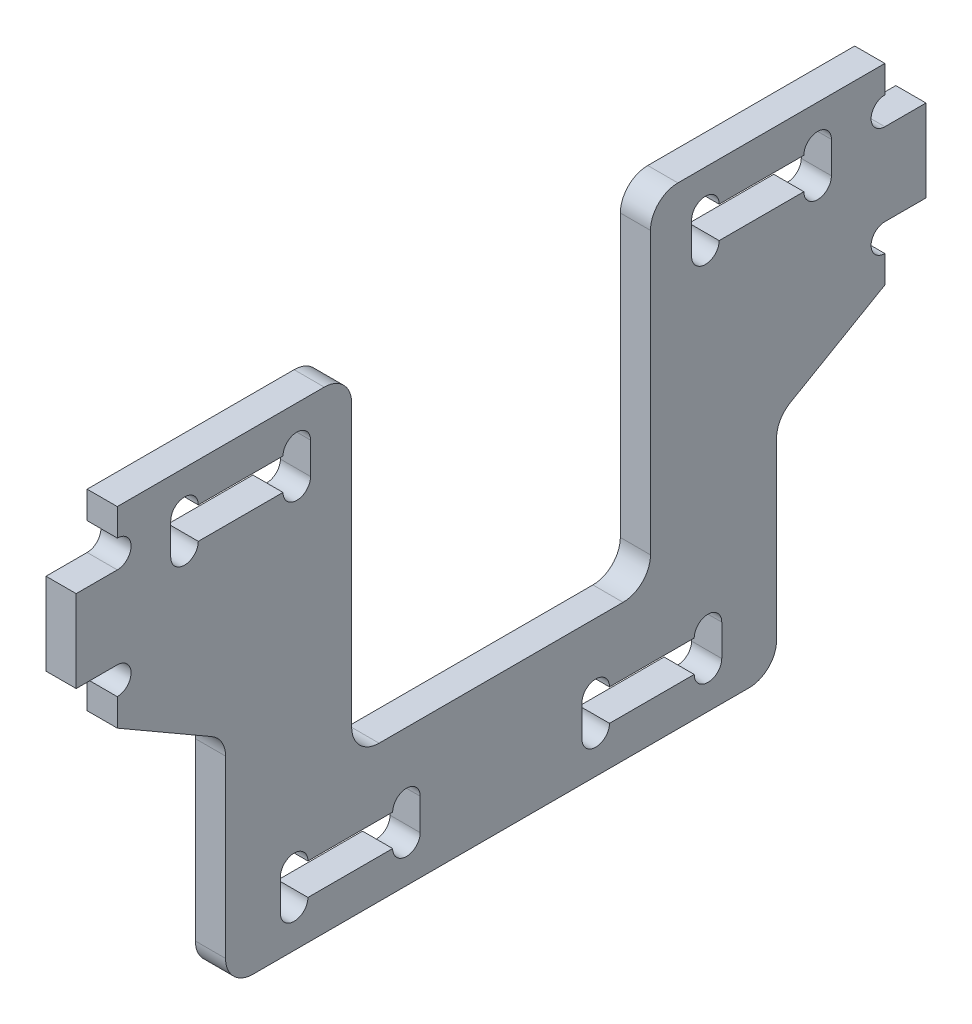
SolidWorks part; units mm, degrees
material "Thornel Mat VMA"
ref_plane "前视基准面" through (0, 0, 0) normal (0, 0, 1) x (1, 0, 0)
ref_plane "上视基准面" through (0, 0, 0) normal (0, 1, 0) x (1, 0, 0)
ref_plane "右视基准面" through (0, 0, 0) normal (1, 0, 0) x (0, 0, -1)
sketch "草图1" plane through (0, 0, 0) normal (1, 0, 0) x (0, 0, -1)
  line L0 (0, 0) -> (0, 15.6623) construction
  line L1 (28, -17.25) -> (-28, -17.25) construction
  line L3 (28, 17.25) -> (10.9, 17.25)
  line L5 (28, -17.25) -> (-28, 17.25) construction
  line L6 (28, 17.25) -> (-28, -17.25) construction
  line L7 (-13.9, 12.1) -> (-24.1, 12.1)
  line L8 (-13.9, 12.1) -> (-13.9, 14.4)
  line L9 (-13.9, 14.4) -> (-24.1, 14.4)
  line L10 (-24.1, 12.1) -> (-24.1, 14.4)
  line L11 (-13.9, 12.1) -> (-24.1, 14.4) construction
  line L12 (-13.9, 14.4) -> (-24.1, 12.1) construction
  line L13 (13.9, 14.4) -> (24.1, 14.4)
  line L14 (24.1, 12.1) -> (24.1, 14.4)
  line L15 (13.9, 12.1) -> (24.1, 12.1)
  line L16 (13.9, 12.1) -> (13.9, 14.4)
  line L17 (19, 14.4) -> (19, 10.7005) construction
  line L18 (0, 0) -> (11.4572, 0) construction
  line L27 (5.9, -12.1) -> (16.1, -14.4) construction
  line L28 (-10.9, 17.25) -> (-10.9, -7.25)
  line L29 (-10.9, -7.25) -> (10.9, -7.25)
  line L30 (10.9, -7.25) -> (10.9, 17.25)
  line L31 (-10.9, 17.25) -> (-28, 17.25)
  line L32 (-28, 13.25) -> (-31, 13.25)
  line L33 (-31, 13.25) -> (-31, 7.25)
  line L34 (-31, 7.25) -> (-28, 7.25)
  line L35 (-31, 10.25) -> (-27.1728, 10.25) construction
  line L36 (-28, 13.25) -> (-28, 17.25)
  line L37 (31, 7.25) -> (28, 7.25)
  line L38 (31, 13.25) -> (31, 7.25)
  line L39 (28, 13.25) -> (31, 13.25)
  line L40 (28, 13.25) -> (28, 17.25)
  line L41 (-28, 3.25) -> (-20.1, -1.3111)
  line L42 (-20.1, -1.3111) -> (-20.1, -17.25)
  line L44 (-28, 3.25) -> (-28, 7.25)
  line L46 (20.1, -1.3111) -> (20.1, -17.25)
  line L47 (28, 3.25) -> (20.1, -1.3111)
  line L48 (28, 3.25) -> (28, 7.25)
  line L49 (-5.9, -14.4) -> (-16.1, -14.4)
  line L50 (-5.9, -14.4) -> (-5.9, -12.1)
  line L51 (-5.9, -12.1) -> (-16.1, -12.1)
  line L52 (-16.1, -14.4) -> (-16.1, -12.1)
  line L53 (-5.9, -14.4) -> (-16.1, -12.1) construction
  line L54 (-5.9, -12.1) -> (-16.1, -14.4) construction
  line L55 (5.9, -14.4) -> (16.1, -12.1) construction
  line L56 (16.1, -14.4) -> (16.1, -12.1)
  line L57 (5.9, -12.1) -> (16.1, -12.1)
  line L58 (5.9, -14.4) -> (5.9, -12.1)
  line L59 (5.9, -14.4) -> (16.1, -14.4)
  line L60 (-20.1, -17.25) -> (20.1, -17.25)
  circle A0 centre (-23.095, 14.4) radius 1.005
  circle A1 centre (-14.905, 14.4) radius 1.005
  circle A2 centre (-23.095, 12.1) radius 1.005
  circle A3 centre (-14.905, 12.1) radius 1.005
  circle A4 centre (14.905, 12.1) radius 1.005
  circle A5 centre (23.095, 12.1) radius 1.005
  circle A6 centre (23.095, 14.4) radius 1.005
  circle A7 centre (14.905, 14.4) radius 1.005
  circle A16 centre (-28, 14.255) radius 1.005
  circle A17 centre (-28, 6.245) radius 1.005
  circle A18 centre (28, 6.245) radius 1.005
  circle A19 centre (28, 14.255) radius 1.005
  circle A20 centre (-6.905, -12.1) radius 1.005
  circle A21 centre (-6.905, -14.4) radius 1.005
  circle A22 centre (-15.095, -14.4) radius 1.005
  circle A23 centre (-15.095, -12.1) radius 1.005
  circle A24 centre (15.095, -12.1) radius 1.005
  circle A25 centre (15.095, -14.4) radius 1.005
  circle A26 centre (6.905, -14.4) radius 1.005
  circle A27 centre (6.905, -12.1) radius 1.005
  point P0 (0, 0)
  point P6 (-19, 13.25)
  point P19 (-11, -13.25)
  point P61 (11, -13.25)
  dimension "D7" = 2.01
  dimension "D1" = 2.3
  dimension "D2" = 10.2
  dimension "D3" = 38
  dimension "D4" = 4
  dimension "D5" = 10.2
  dimension "D6" = 26.5
  dimension "D8" = 10
  dimension "D9" = 56
  dimension "D10" = 3
  dimension "D11" = 3
  dimension "D12" = 6
  dimension "D13" = 7
  dimension "D15" = 4
  dimension "D16" = 2.3
  dimension "D17" = 7
  dimension "D18" = 22
  dimension "D19" = 4
  dimension "D20" = 60
extrude "凸台-拉伸1" add sketch "草图1" along normal blind 2.2
fillet "圆角1" radius 2 8 edges at (1.1, -17.25, 20.1) (1.1, -17.25, -20.1) (1.1, -1.3111, -20.1) (1.1, 17.25, -10.9) (1.1, -7.25, -10.9) (1.1, -7.25, 10.9) (1.1, 17.25, 10.9) (1.1, -1.3111, 20.1)
